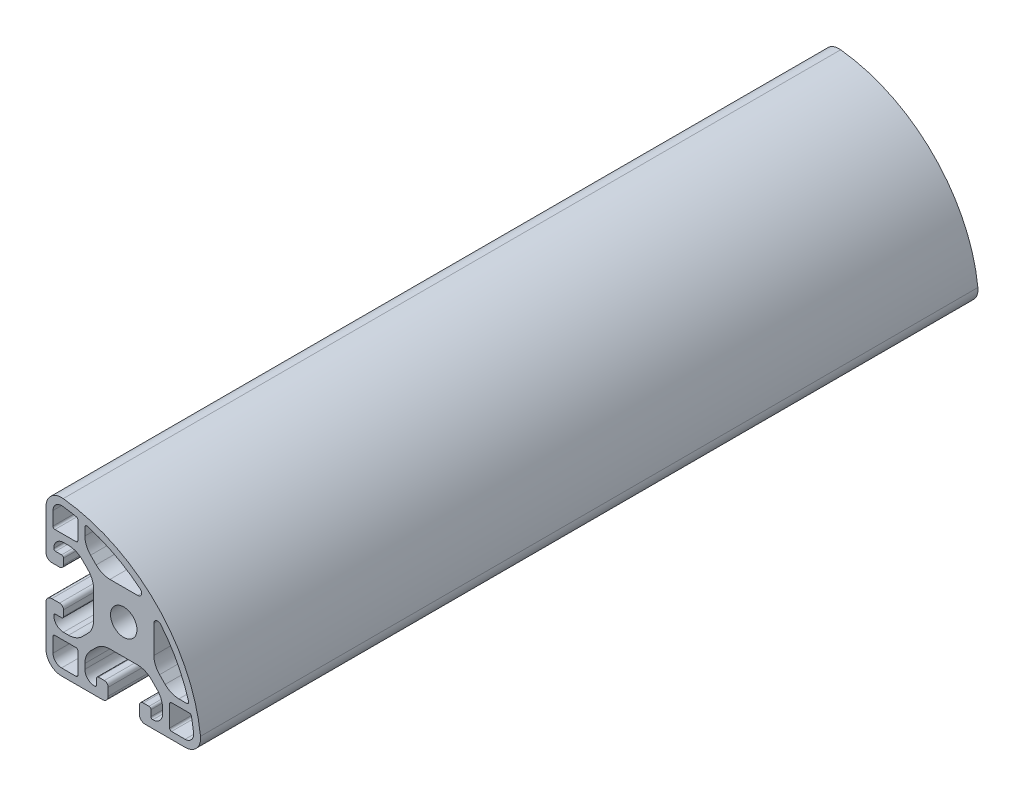
SolidWorks part; units mm, degrees
ref_plane "Piano frontale" through (0, 0, 0) normal (0, 0, 1) x (1, 0, 0)
ref_plane "Piano superiore" through (0, 0, 0) normal (0, 1, 0) x (1, 0, 0)
ref_plane "Piano destro" through (0, 0, 0) normal (1, 0, 0) x (0, 0, -1)
ref_plane "Piano1" through (0, 0, -1034) normal (0, 0, -1) x (-1, 0, 0)
sketch "Schizzo1" plane through (0, 0, -1034) normal (0, 0, -1) x (-1, 0, 0)
  line L0 (-8.2, 32.3) -> (-8.2, 36.9053)
  line L1 (-1.8, 35.7771) -> (-1.8, 32.3)
  line L2 (-2.3, 31.8) -> (-7.7, 31.8)
  line L3 (-4, 1.8) -> (-7.7, 1.8)
  line L4 (-8.2, 2.3) -> (-8.2, 7.7)
  line L5 (-7.7, 8.2) -> (-2.3, 8.2)
  line L6 (-1.8, 7.7) -> (-1.8, 4)
  line L7 (-16, 3.5) -> (-16, 1.5)
  line L8 (-14.5, 0) -> (-4, 0)
  line L9 (0, 4) -> (0, 14.5)
  line L10 (-1.5, 16) -> (-3.5, 16)
  line L11 (-4.5, 15) -> (-4.5, 13.5)
  line L12 (-4, 13) -> (-2.45, 13)
  line L13 (-2, 12.55) -> (-2, 12.5)
  line L14 (-4.5, 10) -> (-5.8076, 10)
  line L15 (-9.3431, 11.4645) -> (-10.7855, 12.9069)
  line L16 (-12.25, 16.4424) -> (-12.25, 23.5576)
  line L17 (-10.7855, 27.0931) -> (-9.3431, 28.5355)
  line L18 (-5.8076, 30) -> (-4.5, 30)
  line L19 (-2, 27.5) -> (-2, 27.45)
  line L20 (-2.45, 27) -> (-4, 27)
  line L21 (-4.5, 26.5) -> (-4.5, 25)
  line L22 (-3.5, 24) -> (-1.5, 24)
  line L23 (0, 25.5) -> (0, 35.7771)
  line L24 (-35.7771, 0) -> (-25.5, 0)
  line L25 (-24, 1.5) -> (-24, 3.5)
  line L26 (-25, 4.5) -> (-26.5, 4.5)
  line L27 (-27, 4) -> (-27, 2.45)
  line L28 (-27.45, 2) -> (-27.5, 2)
  line L29 (-30, 4.5) -> (-30, 5.8076)
  line L30 (-28.5355, 9.3431) -> (-27.0931, 10.7855)
  line L31 (-23.5576, 12.25) -> (-16.4424, 12.25)
  line L32 (-12.9069, 10.7855) -> (-11.4645, 9.3431)
  line L33 (-10, 5.8076) -> (-10, 4.5)
  line L34 (-12.5, 2) -> (-12.55, 2)
  line L35 (-13, 2.45) -> (-13, 4)
  line L36 (-13.5, 4.5) -> (-15, 4.5)
  line L37 (-27.75, 23.6067) -> (-27.75, 16.4424)
  line L38 (-29.2145, 12.9069) -> (-30.6569, 11.4645)
  line L39 (-34.1924, 10) -> (-36.2083, 10)
  line L40 (-10, 36.2083) -> (-10, 34.1924)
  line L41 (-11.4645, 30.6569) -> (-12.9069, 29.2145)
  line L42 (-16.4424, 27.75) -> (-23.6067, 27.75)
  line L43 (-36.9053, 8.2) -> (-32.3, 8.2)
  line L44 (-31.8, 7.7) -> (-31.8, 2.3)
  line L45 (-32.3, 1.8) -> (-35.7771, 1.8)
  arc A0 (-8.2, 36.9053) -> (-7.8021, 37.3947) centre (-7.7, 36.9053) cw
  arc A1 (-7.8021, 37.3947) -> (-4.2444, 37.9635) centre (0, 0) cw
  arc A2 (-4.2444, 37.9635) -> (-1.8, 35.7771) centre (-4, 35.7771) cw
  arc A3 (-1.8, 32.3) -> (-2.3, 31.8) centre (-2.3, 32.3) cw
  arc A4 (-7.7, 31.8) -> (-8.2, 32.3) centre (-7.7, 32.3) cw
  arc A5 (-7.7, 1.8) -> (-8.2, 2.3) centre (-7.7, 2.3) cw
  arc A6 (-8.2, 7.7) -> (-7.7, 8.2) centre (-7.7, 7.7) cw
  arc A7 (-2.3, 8.2) -> (-1.8, 7.7) centre (-2.3, 7.7) cw
  arc A8 (-1.8, 4) -> (-4, 1.8) centre (-4, 4) cw
  circle A9 centre (-20, 20) radius 3.4
  arc A10 (-15, 4.5) -> (-16, 3.5) centre (-15, 3.5) ccw
  arc A11 (-16, 1.5) -> (-14.5, 0) centre (-14.5, 1.5) ccw
  arc A12 (-4, 0) -> (0, 4) centre (-4, 4) ccw
  arc A13 (0, 14.5) -> (-1.5, 16) centre (-1.5, 14.5) ccw
  arc A14 (-3.5, 16) -> (-4.5, 15) centre (-3.5, 15) ccw
  arc A15 (-4.5, 13.5) -> (-4, 13) centre (-4, 13.5) ccw
  arc A16 (-2.45, 13) -> (-2, 12.55) centre (-2.45, 12.55) cw
  arc A17 (-2, 12.5) -> (-4.5, 10) centre (-4.5, 12.5) cw
  arc A18 (-5.8076, 10) -> (-9.3431, 11.4645) centre (-5.8076, 15) cw
  arc A19 (-10.7855, 12.9069) -> (-12.25, 16.4424) centre (-7.25, 16.4424) cw
  arc A20 (-12.25, 23.5576) -> (-10.7855, 27.0931) centre (-7.25, 23.5576) cw
  arc A21 (-9.3431, 28.5355) -> (-5.8076, 30) centre (-5.8076, 25) cw
  arc A22 (-4.5, 30) -> (-2, 27.5) centre (-4.5, 27.5) cw
  arc A23 (-2, 27.45) -> (-2.45, 27) centre (-2.45, 27.45) cw
  arc A24 (-4, 27) -> (-4.5, 26.5) centre (-4, 26.5) ccw
  arc A25 (-4.5, 25) -> (-3.5, 24) centre (-3.5, 25) ccw
  arc A26 (-1.5, 24) -> (0, 25.5) centre (-1.5, 25.5) ccw
  arc A27 (0, 35.7771) -> (-4.4444, 39.7523) centre (-4, 35.7771) ccw
  arc A28 (-4.4444, 39.7523) -> (-39.7523, 4.4444) centre (0, 0) ccw
  arc A29 (-39.7523, 4.4444) -> (-35.7771, 0) centre (-35.7771, 4) ccw
  arc A30 (-25.5, 0) -> (-24, 1.5) centre (-25.5, 1.5) ccw
  arc A31 (-24, 3.5) -> (-25, 4.5) centre (-25, 3.5) ccw
  arc A32 (-26.5, 4.5) -> (-27, 4) centre (-26.5, 4) ccw
  arc A33 (-27, 2.45) -> (-27.45, 2) centre (-27.45, 2.45) cw
  arc A34 (-27.5, 2) -> (-30, 4.5) centre (-27.5, 4.5) cw
  arc A35 (-30, 5.8076) -> (-28.5355, 9.3431) centre (-25, 5.8076) cw
  arc A36 (-27.0931, 10.7855) -> (-23.5576, 12.25) centre (-23.5576, 7.25) cw
  arc A37 (-16.4424, 12.25) -> (-12.9069, 10.7855) centre (-16.4424, 7.25) cw
  arc A38 (-11.4645, 9.3431) -> (-10, 5.8076) centre (-15, 5.8076) cw
  arc A39 (-10, 4.5) -> (-12.5, 2) centre (-12.5, 4.5) cw
  arc A40 (-12.55, 2) -> (-13, 2.45) centre (-12.55, 2.45) cw
  arc A41 (-13, 4) -> (-13.5, 4.5) centre (-13.5, 4) ccw
  arc A42 (-36.2083, 10) -> (-36.6885, 10.6393) centre (-36.2083, 10.5) cw
  arc A43 (-36.6885, 10.6393) -> (-29.5228, 24.2413) centre (0, 0) cw
  arc A44 (-29.5228, 24.2413) -> (-27.75, 23.6067) centre (-28.75, 23.6067) cw
  arc A45 (-27.75, 16.4424) -> (-29.2145, 12.9069) centre (-32.75, 16.4424) cw
  arc A46 (-30.6569, 11.4645) -> (-34.1924, 10) centre (-34.1924, 15) cw
  arc A47 (-10, 34.1924) -> (-11.4645, 30.6569) centre (-15, 34.1924) cw
  arc A48 (-12.9069, 29.2145) -> (-16.4424, 27.75) centre (-16.4424, 32.75) cw
  arc A49 (-23.6067, 27.75) -> (-24.2413, 29.5228) centre (-23.6067, 28.75) cw
  arc A50 (-24.2413, 29.5228) -> (-10.6393, 36.6885) centre (0, 0) cw
  arc A51 (-10.6393, 36.6885) -> (-10, 36.2083) centre (-10.5, 36.2083) cw
  arc A52 (-37.9635, 4.2444) -> (-37.3947, 7.8021) centre (0, 0) cw
  arc A53 (-37.3947, 7.8021) -> (-36.9053, 8.2) centre (-36.9053, 7.7) cw
  arc A54 (-32.3, 8.2) -> (-31.8, 7.7) centre (-32.3, 7.7) cw
  arc A55 (-31.8, 2.3) -> (-32.3, 1.8) centre (-32.3, 2.3) cw
  arc A56 (-35.7771, 1.8) -> (-37.9635, 4.2444) centre (-35.7771, 4) cw
extrude "Estrusione-Estrusione1" add sketch "Schizzo1" against normal blind 200
